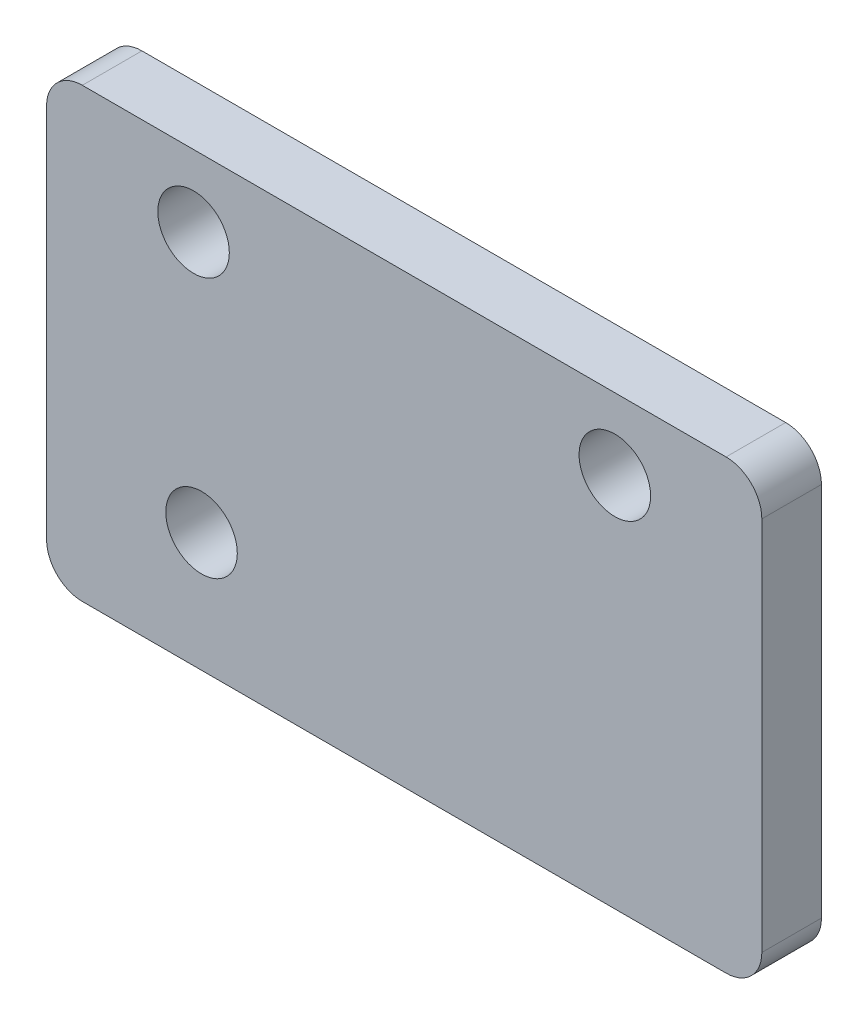
SolidWorks part; units mm, degrees
ref_plane "前视基准面" through (0, 0, 0) normal (0, 0, 1) x (1, 0, 0)
ref_plane "上视基准面" through (0, 0, 0) normal (0, 1, 0) x (1, 0, 0)
ref_plane "右视基准面" through (0, 0, 0) normal (1, 0, 0) x (0, 0, -1)
other "Configuration Table"
sketch "草图1" plane through (0, 0, 0) normal (0, 0, 1) x (1, 0, 0)
  line L0 (0, 0) -> (1.5, 0) construction
  line L2 (-15.5, 27.5) -> (38.5, 27.5)
  line L3 (-18.5, 24.5) -> (-18.5, -7)
  line L4 (-15.5, -10) -> (-8.825, -10)
  line L5 (41.5, 24.5) -> (41.5, -7)
  line L29 (33.3, -10) -> (38.5, -10)
  line L30 (31.175, -10) -> (-8.825, -10)
  line L34 (33.3, -10) -> (31.175, -10)
  arc A20 (38.5, 27.5) -> (41.5, 24.5) centre (38.5, 24.5) cw
  arc A21 (38.5, -10) -> (41.5, -7) centre (38.5, -7) ccw
  arc A22 (-18.5, -7) -> (-15.5, -10) centre (-15.5, -7) ccw
  arc A23 (-15.5, 27.5) -> (-18.5, 24.5) centre (-15.5, 24.5) ccw
  circle A32 centre (21.075, 0) radius 5.2518 construction
  dimension "D4" = 60
  dimension "D13" = 3
  dimension "D7" = 37.5
extrude "凸台-拉伸1" add sketch "草图1" along normal blind 5
sketch "草图2" plane through (0, 0, 5) normal (0, 0, 1) x (1, 0, 0)
  line L0 (21.075, 0) -> (21.075, 6.3806) construction
  line L1 (-15.5, 27.5) -> (38.5, 27.5) construction
  line L2 (11.5, 27.5) -> (11.5, 21.5) construction
  line L5 (29.17, 21.5) -> (-6.17, 21.5) construction
  circle A2 centre (-6.17, 21.5) radius 3
  circle A3 centre (29.17, 21.5) radius 3
  dimension "D1" = 6
  dimension "D5" = 6
  dimension "D3" = 35.34
extrude "切除-拉伸1" cut sketch "草图2" against normal blind 10 contours A2 | A3
sketch "草图4" plane through (0, 0, 5) normal (0, 0, 1) x (1, 0, 0)
  line L0 (41.5, 0) -> (21.5, 0) construction
  line L1 (41.5, 24.5) -> (41.5, -7) construction
  circle A0 centre (-5.5, 0) radius 3
  dimension "D3" = 6
  dimension "D2" = 27
extrude "切除-拉伸2" cut sketch "草图4" against normal blind 10
sketch "草图5" plane through (0, 0, -3) normal (0, 0, 1) x (1, 0, 0)
  circle A0 centre (-87.2851, 32.4678) radius 1.5
  dimension "D1" = 3
